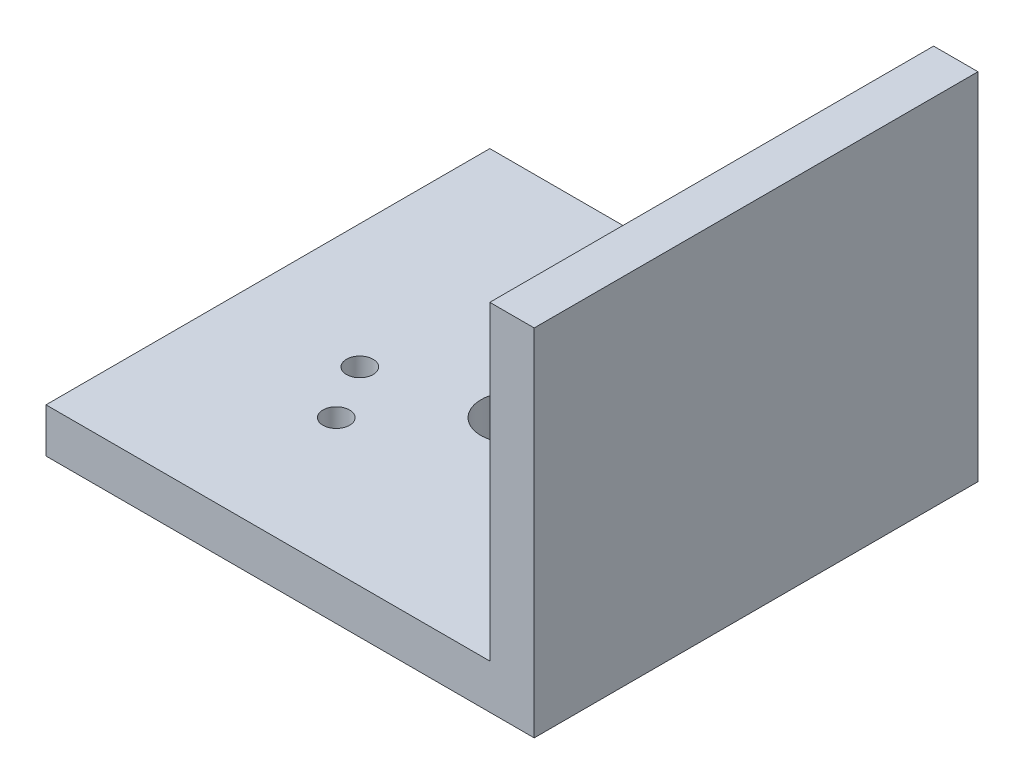
SolidWorks part; units mm, degrees
ref_plane "Front Plane" through (0, 0, 0) normal (0, 0, 1) x (1, 0, 0)
ref_plane "Top Plane" through (0, 0, 0) normal (0, 1, 0) x (1, 0, 0)
ref_plane "Right Plane" through (0, 0, 0) normal (1, 0, 0) x (0, 0, -1)
sketch "Sketch1" plane through (0, 0, 0) normal (0, 0, 1) x (1, 0, 0)
  line L1 (22.5, -2.5) -> (-27.5, -2.5)
  line L3 (22.5, 2.5) -> (-27.5, 2.5)
  line L4 (-27.5, -2.5) -> (-27.5, 2.5)
  line L5 (27.5, -2.5) -> (-27.5, 2.5) construction
  line L6 (27.5, 2.5) -> (-27.5, -2.5) construction
  line L7 (27.5, -2.5) -> (22.5, -2.5)
  line L8 (27.5, -2.5) -> (27.5, 37.5)
  line L9 (27.5, 37.5) -> (22.5, 37.5)
  line L11 (22.5, 2.5) -> (22.5, 37.5)
  point P0 (0, 0)
  dimension "D1" = 55
  dimension "D2" = 5
  dimension "D3" = 40
  dimension "D4" = 5
extrude "Boss-Extrude1" add sketch "Sketch1" along normal mid plane 50
sketch "Sketch2" plane through (0, 2.5, 0) normal (0, 1, 0) x (1, 0, 0)
  line L0 (0, 0) -> (-8.9947, 33.5688) construction
  line L1 (0, -44.7868) -> (0, 44.7868) construction
  line L2 (0, 23.0853) -> (0, 0) construction
  circle A0 centre (0, 0) radius 3.5
  circle A1 centre (0, 0) radius 14 construction
  circle A2 centre (-3.6235, 13.523) radius 1.5
  circle A3 centre (3.6235, 13.523) radius 1.5
  point P7 (-3.6235, 13.523)
  dimension "D1" = 7
  dimension "D3" = 28
  dimension "D4" = 3
  dimension "D2" = 15
extrude "Cut-Extrude1" cut sketch "Sketch2" against normal through all
pattern_circular "CirPattern1" count 3 over 360 about axis through (0, 0, 0) along (0, 1, 0) of "Cut-Extrude1"
